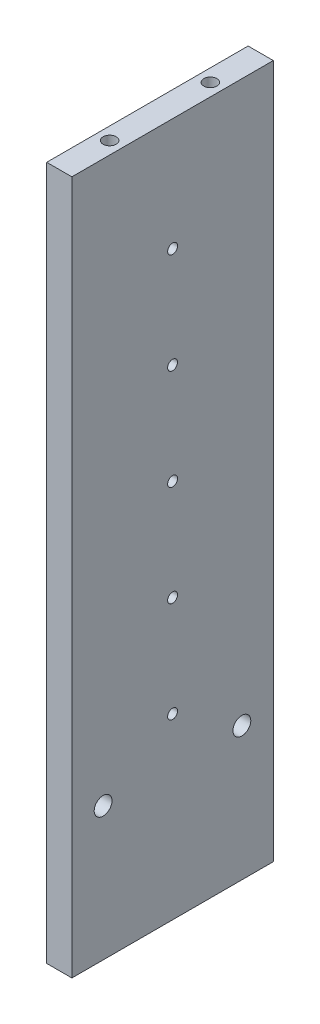
SolidWorks part; units mm, degrees
material "6061 Alloy"
ref_plane "Front Plane" through (0, 0, 0) normal (0, 0, 1) x (1, 0, 0)
ref_plane "Top Plane" through (0, 0, 0) normal (0, 1, 0) x (1, 0, 0)
ref_plane "Right Plane" through (0, 0, 0) normal (1, 0, 0) x (0, 0, -1)
sketch "Sketch1" plane through (0, 0, 0) normal (0, 1, 0) x (1, 0, 0)
  line L1 (0, 0) -> (6.35, 0)
  line L2 (0, 0) -> (0, 38.1)
  line L3 (0, 38.1) -> (6.35, 38.1)
  line L4 (6.35, 0) -> (6.35, 38.1)
  dimension "D1" = 38.1
  dimension "D2" = 6.35
extrude "Boss-Extrude1" add sketch "Sketch1" along normal blind 175
sketch "Sketch2" plane through (0, 175, 0) normal (0, 1, 0) x (1, 0, 0)
  line L0 (0, 0) -> (6.35, 0) construction
  line L1 (6.35, 0) -> (6.35, 38.1) construction
  line L2 (0, 38.1) -> (0, 0) construction
  point P0 (3.175, 31.75)
  point P1 (3.175, 6.35)
  dimension "D1" = 25.4
  dimension "D2" = 6.35
  dimension "D3" = 3.175
  dimension "D4" = 3.175
hole_wizard "M4x0.7 Tapped Hole1" positions "Sketch4" profile "Sketch3" tap size "M4x0.7" standard "ANSI Metric"
sketch "Sketch4" plane through (0, 175, 0) normal (0, 1, 0) x (1, 0, 0)
  point P0 (3.175, 31.75)
  point P3 (3.175, 6.35)
sketch "Sketch3" plane through (3.175, 175, -31.75) normal (1, 0, 0) x (0, 0, 1)
  line L0 (0, 0) -> (0, 11.0914)
  line L1 (0, 11.0914) -> (1.65, 10.1)
  line L2 (1.65, 10.1) -> (1.65, 0)
  line L5 (1.65, 0) -> (0, 0)
  line L10 (0, 11.0914) -> (-1.65, 10.1) construction
  line L11 (0, -6.35) -> (0, 107.95) construction
  dimension "Tap Drill Dia." = 3.3
  dimension "Tap Drill Depth" = 10.1
  dimension "Drill Angle" = 118
cosmetic thread "Hole Thread8" parameters "D1"=8, "D2"=4
cosmetic thread "Hole Thread9" parameters "D1"=8, "D2"=4
ref_plane "Plane1" through (0, 73.66, 0) normal (0, 1, 0) x (1, 0, 0)
sketch "Sketch5" plane through (6.35, 0, 0) normal (1, 0, 0) x (0, 0, -1)
  line L0 (0, 0) -> (38.1, 0) construction
  line L1 (0, 175) -> (0, 0) construction
  point P0 (19.05, 121.2)
  point P1 (19.05, 95.8)
  point P2 (19.05, 70.4)
  point P3 (19.05, 45)
  point P4 (19.05, 0)
  point P9 (19.05, 146.6)
  dimension "D1" = 25.4
  dimension "D2" = 25.4
  dimension "D3" = 25.4
  dimension "D4" = 45
  dimension "D5" = 19.05
  dimension "D6" = 25.4
hole_wizard "M3x0.5 Tapped Hole1" positions "Sketch7" profile "Sketch6" tap size "M3x0.5" standard "ANSI Metric" end condition through all
sketch "Sketch7" plane through (6.35, 0, 0) normal (1, 0, 0) x (0, 0, -1)
  point P0 (19.05, 121.2)
  point P3 (19.05, 95.8)
  point P7 (19.05, 70.4)
  point P10 (19.05, 45)
  point P14 (19.05, 146.6)
sketch "Sketch6" plane through (6.35, 121.2, -19.05) normal (0, 1, 0) x (0, 0, -1)
  line L0 (0, 0) -> (0, 6.35)
  line L1 (0, 6.35) -> (1.25, 6.35)
  line L2 (1.25, 6.35) -> (1.25, 0)
  line L5 (1.25, 0) -> (0, 0)
  line L11 (0, -6.35) -> (0, 107.95) construction
  dimension "Thru Tap Drill Dia." = 2.5
  dimension "Thru Tap Drill Depth" = 6.35
cosmetic thread "Hole Thread3" parameters "D2"=3
cosmetic thread "Hole Thread4" parameters "D2"=3
cosmetic thread "Hole Thread5" parameters "D2"=3
cosmetic thread "Hole Thread6" parameters "D2"=3
cosmetic thread "Hole Thread7" parameters "D2"=3
sketch "Sketch9" plane through (6.35, 0, 0) normal (1, 0, 0) x (0, 0, -1)
  line L1 (0, 175) -> (-6.35, 175)
  line L2 (0, 175) -> (0, 0)
  line L3 (0, 0) -> (-6.35, 0)
  line L4 (-6.35, 175) -> (-6.35, 0)
  line L5 (38.1, 175) -> (44.45, 175)
  line L6 (38.1, 175) -> (38.1, 0)
  line L7 (38.1, 0) -> (44.45, 0)
  line L8 (44.45, 175) -> (44.45, 0)
extrude "Boss-Extrude2" add sketch "Sketch9" against normal blind 6.35
sketch "Sketch8" plane through (6.35, 0, 0) normal (1, 0, 0) x (0, 0, -1)
  line L0 (-6.35, 0) -> (44.45, 0) construction
  circle A0 centre (36.524, 33.675) radius 2.25
  circle A1 centre (1.524, 33.675) radius 2.25
  dimension "D1" = 33.675
  dimension "D2" = 35
extrude "Cut-Extrude1" cut sketch "Sketch8" against normal through all
sketch "Sketch10" plane through (0, 0, 0) normal (0, -1, 0) x (1, 0, 0)
  point P5 (3.175, -6.35)
  point P8 (3.175, -31.75)
hole_wizard "M4x0.7 Tapped Hole2" positions "Sketch12" profile "Sketch11" tap size "M4x0.7" standard "ANSI Metric"
sketch "Sketch12" plane through (0, 0, 0) normal (0, -1, 0) x (-1, 0, 0)
  point P0 (-3.175, 6.35)
  point P3 (-3.175, 31.75)
sketch "Sketch11" plane through (3.175, 0, -6.35) normal (1, 0, 0) x (0, 0, -1)
  line L0 (0, 0) -> (0, 26.3914)
  line L1 (0, 26.3914) -> (1.65, 25.4)
  line L2 (1.65, 25.4) -> (1.65, 0)
  line L5 (1.65, 0) -> (0, 0)
  line L10 (0, 26.3914) -> (-1.65, 25.4) construction
  line L11 (0, -6.35) -> (0, 107.95) construction
  dimension "Tap Drill Dia." = 3.3
  dimension "Tap Drill Depth" = 25.4
  dimension "Drill Angle" = 118
cosmetic thread "Hole Thread10" parameters "D1"=20, "D2"=4
cosmetic thread "Hole Thread11" parameters "D1"=20, "D2"=4
